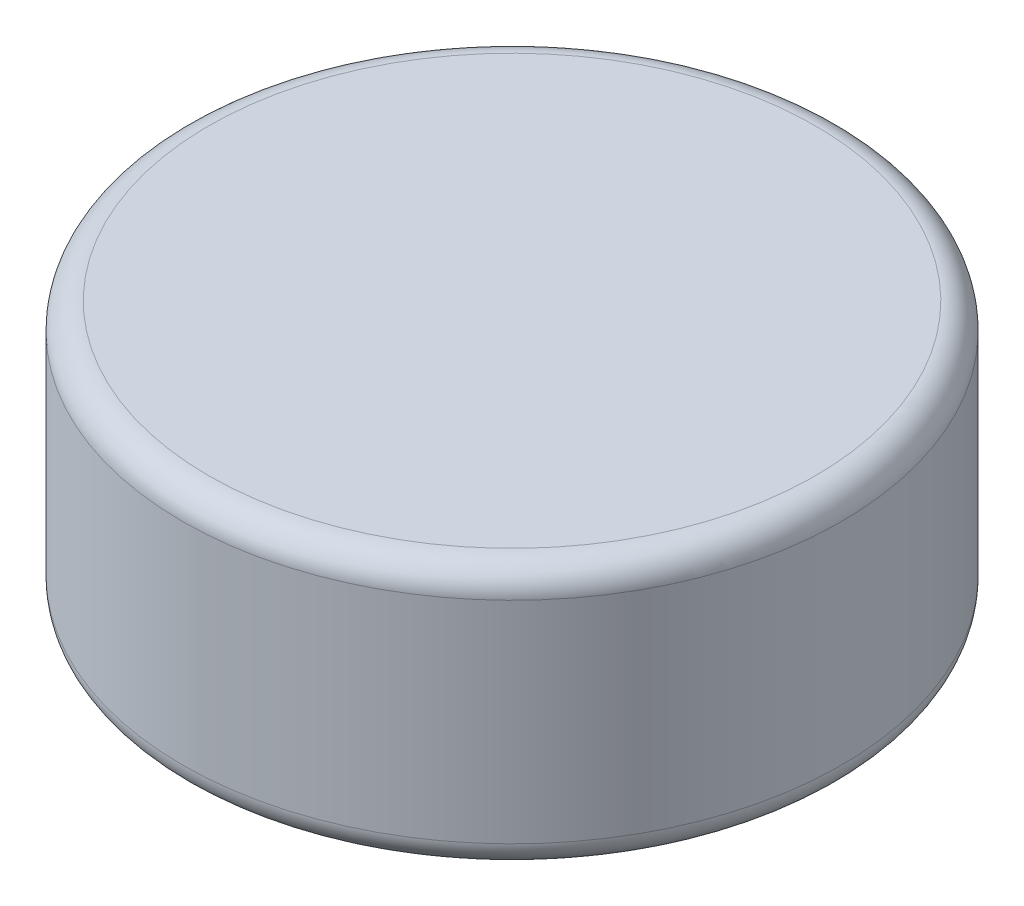
SolidWorks part; units mm, degrees
material "Nickel"
ref_plane "Front Plane" through (0, 0, 0) normal (0, 0, 1) x (1, 0, 0)
ref_plane "Top Plane" through (0, 0, 0) normal (0, 1, 0) x (1, 0, 0)
ref_plane "Right Plane" through (0, 0, 0) normal (1, 0, 0) x (0, 0, -1)
sketch "Sketch1" plane through (0, 0, 0) normal (0, 1, 0) x (1, 0, 0)
  circle A0 centre (0, 0) radius 2.5
  dimension "D1" = 5
extrude "Boss-Extrude1" add sketch "Sketch1" along normal mid plane 2
fillet "Fillet1" radius 0.2 2 edges at (0, -1, 2.5) (0, 1, 2.5)
